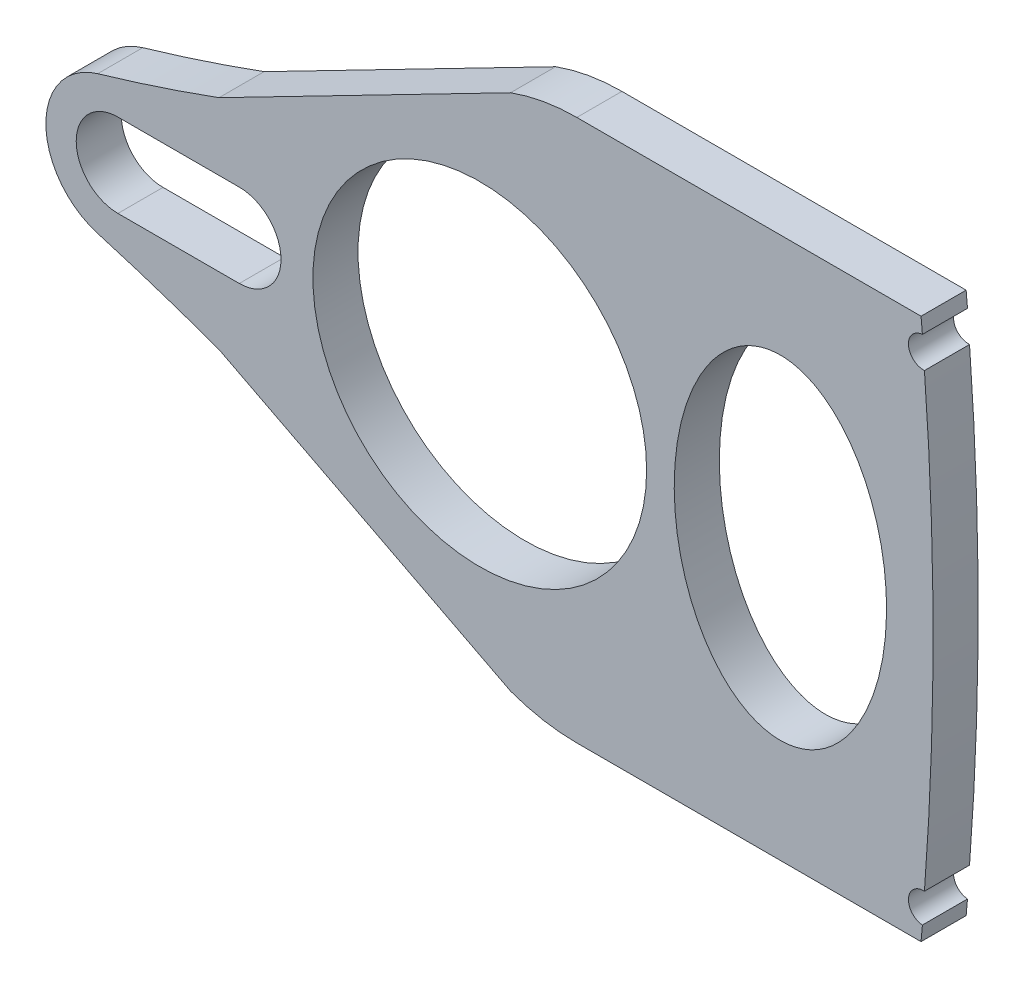
SolidWorks part; units mm, degrees
ref_plane "Front Plane" through (0, 0, 0) normal (0, 0, 1) x (1, 0, 0)
ref_plane "Top Plane" through (0, 0, 0) normal (0, 1, 0) x (1, 0, 0)
ref_plane "Right Plane" through (0, 0, 0) normal (1, 0, 0) x (0, 0, -1)
sketch "Sketch1" plane through (0, 0, 0) normal (0, 0, 1) x (1, 0, 0)
  line L0 (-7.9477, 25.9479) -> (-30.8487, 25.9491)
  line L1 (-35.2546, 25.168) -> (-54.6534, 15.1845)
  line L5 (-61.3782, 10.7044) -> (-53.3047, 10.7044)
  line L6 (-66.1719, 7.9291) -> (-7.3465, 7.9291) construction
  line L7 (-61.3782, 5.1538) -> (-53.3047, 5.1538)
  line L8 (-35.2546, -9.3098) -> (-54.6534, 0.6737)
  line L9 (-7.9477, -10.0897) -> (-30.8487, -10.0909)
  arc A2 (-7.7221, -7.0709) -> (-7.7221, 22.9291) centre (-202.995, 7.9291) ccw
  arc A3 (-8.7664, 24.1347) -> (-7.7221, 22.9291) centre (-7.7768, 23.9368) ccw
  arc A4 (-7.8575, 24.9428) -> (-8.7664, 24.1347) centre (-7.7768, 23.9368) ccw
  arc A5 (-7.8575, 24.9428) -> (-7.9477, 25.9479) centre (-202.995, 7.9291) ccw
  arc A6 (-30.8487, 25.9491) -> (-35.2546, 25.168) centre (-30.8487, 13.1324) ccw
  arc A7 (-62.7243, 12.5299) -> (-54.6534, 15.1845) centre (-98.7124, 135.5407) ccw
  arc A8 (-62.7243, 12.5299) -> (-62.7243, 3.3283) centre (-61.3782, 7.9291) ccw
  circle A12 centre (-37.3047, 7.9291) radius 11.1011
  arc A13 (-61.3782, 10.7044) -> (-61.3782, 5.1538) centre (-61.3782, 7.9291) ccw
  arc A14 (-53.3047, 5.1538) -> (-53.3047, 10.7044) centre (-53.3047, 7.9291) ccw
  arc A15 (-62.7243, 3.3283) -> (-54.6534, 0.6737) centre (-98.7124, -119.6825) cw
  arc A16 (-30.8487, -10.0909) -> (-35.2546, -9.3098) centre (-30.8487, 2.7258) cw
  arc A17 (-7.8575, -9.0846) -> (-7.9477, -10.0897) centre (-202.995, 7.9291) cw
  arc A18 (-7.8575, -9.0846) -> (-8.7664, -8.2765) centre (-7.7768, -8.0786) cw
  arc A19 (-8.7664, -8.2765) -> (-7.7221, -7.0709) centre (-7.7768, -8.0786) cw
  ellipse E0 centre (-17.3047, 7.9291) end of major axis (-17.3047, -3.172) minor radius 7.0643
  point P29 (-24.3691, 7.9291)
  point P42 (-37.3047, 7.9291)
  point P45 (-17.3047, 7.9291)
  point P50 (-10.2404, 7.9291)
  dimension "D3" = 30
  dimension "D4" = 1.0092
  dimension "D1" = 16
  dimension "D2" = 20
  dimension "D5" = 2.0182
extrude "Boss-Extrude1" add sketch "Sketch1" along normal blind 3
